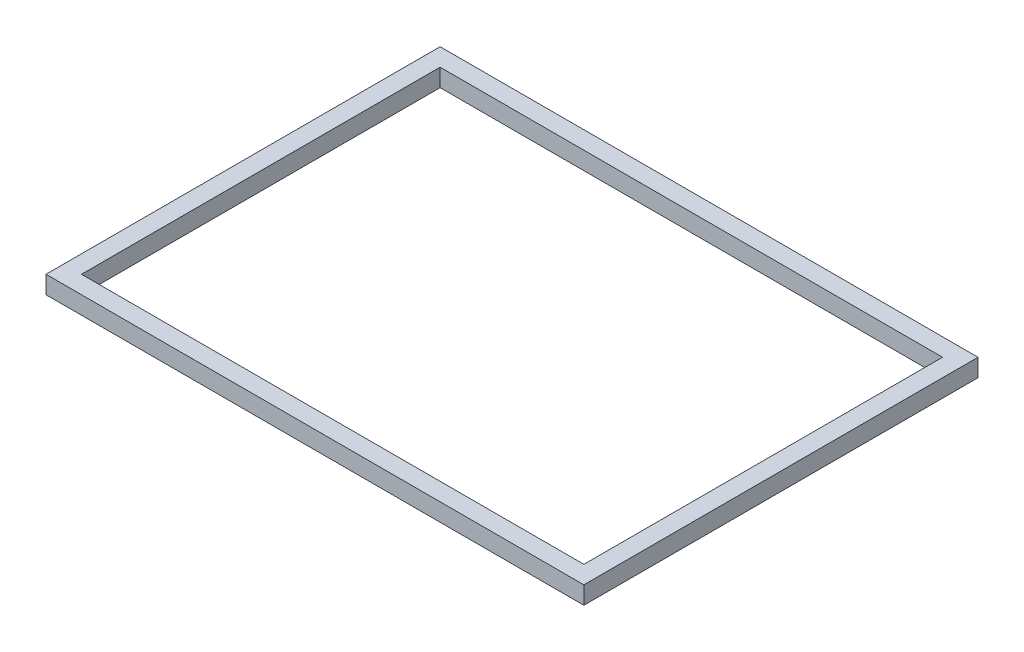
SolidWorks part; units mm, degrees
ref_plane "Front Plane" through (0, 0, 0) normal (0, 0, 1) x (1, 0, 0)
ref_plane "Top Plane" through (0, 0, 0) normal (0, 1, 0) x (1, 0, 0)
ref_plane "Right Plane" through (0, 0, 0) normal (1, 0, 0) x (0, 0, -1)
sketch "Sketch1" plane through (0, 0, 0) normal (0, 1, 0) x (1, 0, 0)
  line L1 (-427.0375, 304.8375) -> (427.0375, 304.8375)
  line L2 (-427.0375, 304.8375) -> (-427.0375, -304.8375)
  line L3 (-427.0375, -304.8375) -> (427.0375, -304.8375)
  line L4 (427.0375, 304.8375) -> (427.0375, -304.8375)
  line L5 (-427.0375, 304.8375) -> (427.0375, -304.8375) construction
  line L6 (-427.0375, -304.8375) -> (427.0375, 304.8375) construction
  line L7 (-457.2, 335) -> (457.2, 335)
  line L8 (-457.2, 335) -> (-457.2, -335)
  line L9 (-457.2, -335) -> (457.2, -335)
  line L10 (457.2, 335) -> (457.2, -335)
  line L11 (-457.2, 335) -> (457.2, -335) construction
  line L12 (-457.2, -335) -> (457.2, 335) construction
  point P0 (0, 0)
  point P6 (0, 0)
  dimension "D1" = 30.1625
  dimension "D2" = 670
  dimension "D3" = 914.4
  dimension "D4" = 30.1625
extrude "Boss-Extrude1" add sketch "Sketch1" along normal blind 30.1625
equation "\"D4@Sketch1\"=\"D1@Sketch1\""
